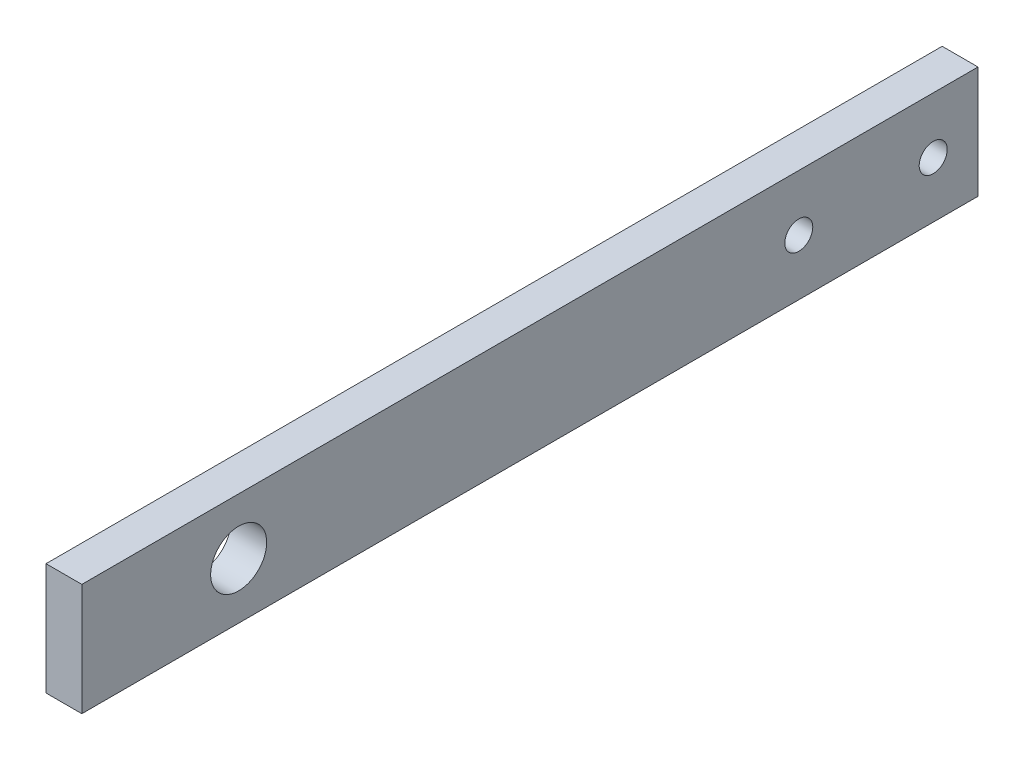
SolidWorks part; units mm, degrees
material "1060 Alloy"
ref_plane "Front Plane" through (0, 0, 0) normal (0, 0, 1) x (1, 0, 0)
ref_plane "Top Plane" through (0, 0, 0) normal (0, 1, 0) x (1, 0, 0)
ref_plane "Right Plane" through (0, 0, 0) normal (1, 0, 0) x (0, 0, -1)
sketch "Sketch1" plane through (0, 0, 0) normal (1, 0, 0) x (0, 0, -1)
  line L1 (0, 0) -> (50.8, 0)
  line L2 (0, 0) -> (0, 6.35)
  line L3 (0, 6.35) -> (50.8, 6.35)
  line L4 (50.8, 0) -> (50.8, 6.35)
  dimension "D1" = 6.35
  dimension "D2" = 50.8
extrude "Boss-Extrude1" add sketch "Sketch1" along normal blind 2.032
hole_wizard "1/16 (0.0625) Diameter Hole1" positions "Sketch3" profile "Sketch2" hole size "1/16" standard "ANSI Inch"
sketch "Sketch3" plane through (2.032, 0, 0) normal (1, 0, 0) x (0, 0, -1)
  line L0 (50.8, 0) -> (50.8, 6.35) construction
  point P0 (40.64, 3.175)
  point P2 (48.26, 3.175)
  point P5 (50.8, 3.175)
  dimension "D1" = 0
  dimension "D2" = 0
  dimension "D3" = 7.62
  dimension "D4" = 2.54
sketch "Sketch2" plane through (2.032, 3.175, -40.64) normal (0, 1, 0) x (0, 0, -1)
  line L0 (0, 0) -> (0, 70.5809)
  line L1 (0, 70.5809) -> (0.7937, 70.104)
  line L2 (0.7937, 70.104) -> (0.7937, 0)
  line L5 (0.7937, 0) -> (0, 0)
  line L10 (0, 70.5809) -> (-0.7938, 70.104) construction
  line L11 (0, -6.35) -> (0, 107.95) construction
  dimension "Hole Dia." = 1.5875
  dimension "Hole Depth" = 70.104
  dimension "Drill Angle" = 118
hole_wizard "1/8 (0.125) Diameter Hole1" positions "Sketch5" profile "Sketch4" hole size "1/8" standard "ANSI Inch"
sketch "Sketch5" plane through (2.032, 0, 0) normal (1, 0, 0) x (0, 0, -1)
  circle A0 centre (40.64, 3.175) radius 0.7937 construction
  point P0 (8.89, 3.175)
  dimension "D1" = 31.75
  dimension "D2" = 0
sketch "Sketch4" plane through (2.032, 3.175, -8.89) normal (0, 1, 0) x (0, 0, -1)
  line L0 (0, 0) -> (0, 71.0579)
  line L1 (0, 71.0579) -> (1.5875, 70.104)
  line L2 (1.5875, 70.104) -> (1.5875, 0)
  line L5 (1.5875, 0) -> (0, 0)
  line L10 (0, 71.0579) -> (-1.5875, 70.104) construction
  line L11 (0, -6.35) -> (0, 107.95) construction
  dimension "Hole Dia." = 3.175
  dimension "Hole Depth" = 70.104
  dimension "Drill Angle" = 118
